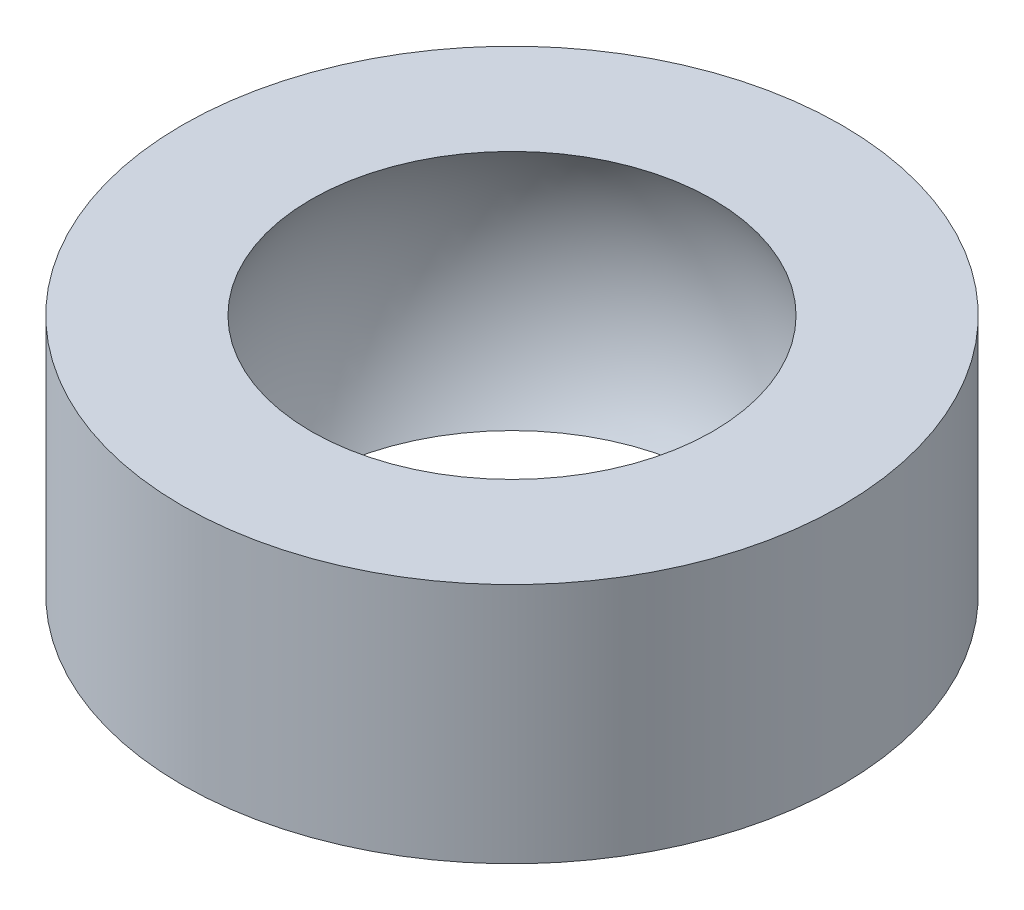
SolidWorks part; units mm, degrees
ref_plane "Спереди" through (0, 0, 0) normal (0, 0, 1) x (1, 0, 0)
ref_plane "Сверху" through (0, 0, 0) normal (0, 1, 0) x (1, 0, 0)
ref_plane "Справа" through (0, 0, 0) normal (1, 0, 0) x (0, 0, -1)
sketch "Эскиз1" plane through (0, 0, 0) normal (0, 1, 0) x (1, 0, 0)
  circle A0 centre (0, 0) radius 9
  dimension "D1" = 18
extrude "Бобышка-Вытянуть1" add sketch "Эскиз1" along normal mid plane 6.6
sketch "Эскиз2" plane through (0, 0, 0) normal (0, 0, 1) x (1, 0, 0)
  line L0 (0, 0) -> (0, 9.156) construction
  line L1 (0, 6.4) -> (0, -6.4)
  arc A0 (0, -6.4) -> (0, 6.4) centre (0, 0) ccw
  arc A1 (0, 6.4) -> (0, -6.4) centre (0, 0) ccw construction
  dimension "D1" = 12.8
revolve "Вырез-Повернуть1" cut sketch "Эскиз2" angle 360 about L0
equation "\"Ball_bearing_D\"= 12.7"
equation "\"Ball_bearing_h1\"= 9"
equation "\"Ball_bearing_d1\"= 5.9"
equation "\"Ball_bearing_d2\"= 18"
equation "\"Ball_bearing_h2\"= 6.6"
equation "\"Brake_tube_d1\"= 2"
equation "\"Brake_tube_d2\"= 5"
equation "\"Brake_tube_h\"= 20"
equation "\"D1@Эскиз1\"=\"Ball_bearing_d2\""
equation "\"D1@Бобышка-Вытянуть1\"=\"Ball_bearing_h2\""
equation "\"D1@Эскиз2\"=\"Ball_bearing_D\"+0.1"
